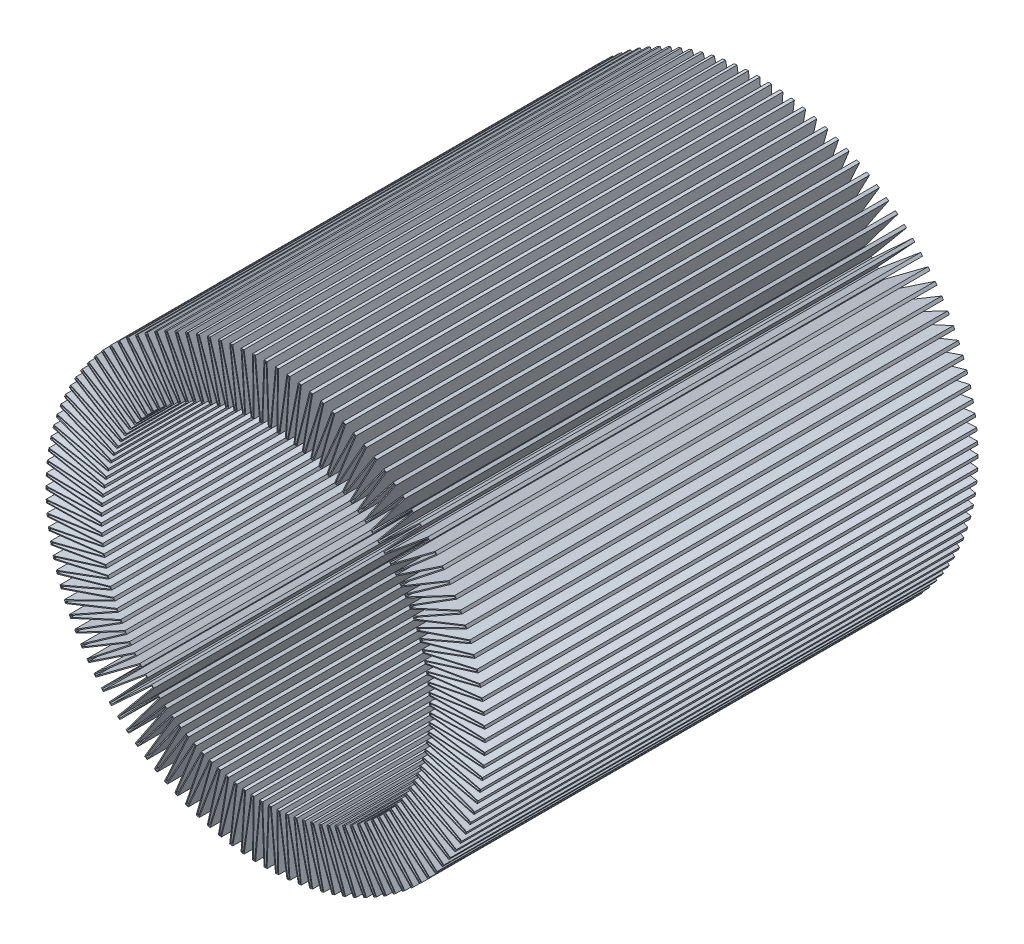
SolidWorks part; units mm, degrees
ref_plane "Front Plane" through (0, 0, 0) normal (0, 0, 1) x (1, 0, 0)
ref_plane "Top Plane" through (0, 0, 0) normal (0, 1, 0) x (1, 0, 0)
ref_plane "Right Plane" through (0, 0, 0) normal (1, 0, 0) x (0, 0, -1)
sketch "Sketch1" plane through (0, 0, 0) normal (0, 0, 1) x (1, 0, 0)
  line L0 (200.3975, -1.3849) -> (200.3975, 1.3849)
  line L1 (200.3975, 1.3849) -> (150.3615, 3.3121)
  line L2 (150.3615, 3.3121) -> (150.3288, 4.5618)
  line L3 (150.3288, 4.5618) -> (200.1953, 9.105)
  line L4 (200.1953, 9.105) -> (200.0504, 11.871)
  line L5 (200.0504, 11.871) -> (149.9821, 11.1769)
  line L6 (149.9821, 11.1769) -> (149.884, 12.4231)
  line L7 (149.884, 12.4231) -> (199.4445, 19.5699)
  line L8 (199.4445, 19.5699) -> (199.1549, 22.3245)
  line L9 (199.1549, 22.3245) -> (149.1916, 19.011)
  line L10 (149.1916, 19.011) -> (149.0284, 20.2504)
  line L11 (149.0284, 20.2504) -> (198.1469, 29.9812)
  line L12 (198.1469, 29.9812) -> (197.7136, 32.7169)
  line L13 (197.7136, 32.7169) -> (147.9922, 26.793)
  line L14 (147.9922, 26.793) -> (147.7644, 28.0222)
  line L15 (147.7644, 28.0222) -> (196.3063, 40.3104)
  line L16 (196.3063, 40.3104) -> (195.7304, 43.0196)
  line L17 (195.7304, 43.0196) -> (146.3871, 34.5016)
  line L18 (146.3871, 34.5016) -> (146.0953, 35.7172)
  line L19 (146.0953, 35.7172) -> (193.9276, 50.529)
  line L20 (193.9276, 50.529) -> (193.2107, 53.2044)
  line L21 (193.2107, 53.2044) -> (144.3808, 42.1156)
  line L22 (144.3808, 42.1156) -> (144.0258, 43.3143)
  line L23 (144.0258, 43.3143) -> (191.0173, 60.6091)
  line L24 (191.0173, 60.6091) -> (190.1614, 63.2433)
  line L25 (190.1614, 63.2433) -> (141.9788, 49.6142)
  line L26 (141.9788, 49.6142) -> (141.5615, 50.7926)
  line L27 (141.5615, 50.7926) -> (187.5835, 70.5231)
  line L28 (187.5835, 70.5231) -> (186.5909, 73.1089)
  line L29 (186.5909, 73.1089) -> (139.1876, 56.9768)
  line L30 (139.1876, 56.9768) -> (138.7092, 58.1318)
  line L31 (138.7092, 58.1318) -> (183.6355, 80.2439)
  line L32 (183.6355, 80.2439) -> (182.5089, 82.7742)
  line L33 (182.5089, 82.7742) -> (136.0149, 64.1833)
  line L34 (136.0149, 64.1833) -> (135.4767, 65.3116)
  line L35 (135.4767, 65.3116) -> (179.1842, 89.7446)
  line L36 (179.1842, 89.7446) -> (177.9268, 92.2125)
  line L37 (177.9268, 92.2125) -> (132.4694, 71.2138)
  line L38 (132.4694, 71.2138) -> (131.8729, 72.3124)
  line L39 (131.8729, 72.3124) -> (174.2418, 98.9994)
  line L40 (174.2418, 98.9994) -> (172.8569, 101.3981)
  line L41 (172.8569, 101.3981) -> (128.5608, 78.0491)
  line L42 (128.5608, 78.0491) -> (127.9076, 79.115)
  line L43 (127.9076, 79.115) -> (168.8217, 107.9828)
  line L44 (168.8217, 107.9828) -> (167.3132, 110.3058)
  line L45 (167.3132, 110.3058) -> (124.2999, 84.6705)
  line L46 (124.2999, 84.6705) -> (123.5918, 85.7007)
  line L47 (123.5918, 85.7007) -> (162.939, 116.6703)
  line L48 (162.939, 116.6703) -> (161.311, 118.9111)
  line L49 (161.311, 118.9111) -> (119.6982, 91.0598)
  line L50 (119.6982, 91.0598) -> (118.9372, 92.0516)
  line L51 (118.9372, 92.0516) -> (156.6096, 125.038)
  line L52 (156.6096, 125.038) -> (154.8666, 127.1905)
  line L53 (154.8666, 127.1905) -> (114.7685, 97.1995)
  line L54 (114.7685, 97.1995) -> (113.9566, 98.1501)
  line L55 (113.9566, 98.1501) -> (149.851, 133.0629)
  line L56 (149.851, 133.0629) -> (147.9977, 135.1213)
  line L57 (147.9977, 135.1213) -> (109.5242, 103.0728)
  line L58 (109.5242, 103.0728) -> (108.6636, 103.9796)
  line L59 (108.6636, 103.9796) -> (142.6817, 140.7232)
  line L60 (142.6817, 140.7232) -> (140.7232, 142.6817)
  line L61 (140.7232, 142.6817) -> (103.9796, 108.6636)
  line L62 (103.9796, 108.6636) -> (103.0728, 109.5242)
  line L63 (103.0728, 109.5242) -> (135.1213, 147.9977)
  line L64 (135.1213, 147.9977) -> (133.0629, 149.851)
  line L65 (133.0629, 149.851) -> (98.1501, 113.9566)
  line L66 (98.1501, 113.9566) -> (97.1995, 114.7685)
  line L67 (97.1995, 114.7685) -> (127.1905, 154.8666)
  line L68 (127.1905, 154.8666) -> (125.038, 156.6096)
  line L69 (125.038, 156.6096) -> (92.0516, 118.9372)
  line L70 (92.0516, 118.9372) -> (91.0598, 119.6982)
  line L71 (91.0598, 119.6982) -> (118.9111, 161.311)
  line L72 (118.9111, 161.311) -> (116.6703, 162.939)
  line L73 (116.6703, 162.939) -> (85.7007, 123.5918)
  line L74 (85.7007, 123.5918) -> (84.6705, 124.2999)
  line L75 (84.6705, 124.2999) -> (110.3058, 167.3132)
  line L76 (110.3058, 167.3132) -> (107.9828, 168.8217)
  line L77 (107.9828, 168.8217) -> (79.115, 127.9076)
  line L78 (79.115, 127.9076) -> (78.0491, 128.5608)
  line L79 (78.0491, 128.5608) -> (101.3981, 172.8569)
  line L80 (101.3981, 172.8569) -> (98.9994, 174.2418)
  line L81 (98.9994, 174.2418) -> (72.3124, 131.8729)
  line L82 (72.3124, 131.8729) -> (71.2138, 132.4694)
  line L83 (71.2138, 132.4694) -> (92.2125, 177.9268)
  line L84 (92.2125, 177.9268) -> (89.7446, 179.1842)
  line L85 (89.7446, 179.1842) -> (65.3116, 135.4767)
  line L86 (65.3116, 135.4767) -> (64.1833, 136.0149)
  line L87 (64.1833, 136.0149) -> (82.7742, 182.5089)
  line L88 (82.7742, 182.5089) -> (80.2439, 183.6355)
  line L89 (80.2439, 183.6355) -> (58.1318, 138.7092)
  line L90 (58.1318, 138.7092) -> (56.9768, 139.1876)
  line L91 (56.9768, 139.1876) -> (73.1089, 186.5909)
  line L92 (73.1089, 186.5909) -> (70.5231, 187.5835)
  line L93 (70.5231, 187.5835) -> (50.7926, 141.5615)
  line L94 (50.7926, 141.5615) -> (49.6142, 141.9788)
  line L95 (49.6142, 141.9788) -> (63.2433, 190.1614)
  line L96 (63.2433, 190.1614) -> (60.6091, 191.0173)
  line L97 (60.6091, 191.0173) -> (43.3143, 144.0258)
  line L98 (43.3143, 144.0258) -> (42.1156, 144.3808)
  line L99 (42.1156, 144.3808) -> (53.2044, 193.2107)
  line L100 (53.2044, 193.2107) -> (50.529, 193.9276)
  line L101 (50.529, 193.9276) -> (35.7172, 146.0953)
  line L102 (35.7172, 146.0953) -> (34.5016, 146.3871)
  line L103 (34.5016, 146.3871) -> (43.0196, 195.7304)
  line L104 (43.0196, 195.7304) -> (40.3104, 196.3063)
  line L105 (40.3104, 196.3063) -> (28.0222, 147.7644)
  line L106 (28.0222, 147.7644) -> (26.793, 147.9922)
  line L107 (26.793, 147.9922) -> (32.7169, 197.7136)
  line L108 (32.7169, 197.7136) -> (29.9812, 198.1469)
  line L109 (29.9812, 198.1469) -> (20.2504, 149.0284)
  line L110 (20.2504, 149.0284) -> (19.011, 149.1916)
  line L111 (19.011, 149.1916) -> (22.3245, 199.1549)
  line L112 (22.3245, 199.1549) -> (19.5699, 199.4445)
  line L113 (19.5699, 199.4445) -> (12.4231, 149.884)
  line L114 (12.4231, 149.884) -> (11.1769, 149.9821)
  line L115 (11.1769, 149.9821) -> (11.871, 200.0504)
  line L116 (11.871, 200.0504) -> (9.105, 200.1953)
  line L117 (9.105, 200.1953) -> (4.5618, 150.3288)
  line L118 (4.5618, 150.3288) -> (3.3121, 150.3615)
  line L119 (3.3121, 150.3615) -> (1.3849, 200.3975)
  line L120 (1.3849, 200.3975) -> (-1.3849, 200.3975)
  line L121 (-1.3849, 200.3975) -> (-3.3121, 150.3615)
  line L122 (-3.3121, 150.3615) -> (-4.5618, 150.3288)
  line L123 (-4.5618, 150.3288) -> (-9.105, 200.1953)
  line L124 (-9.105, 200.1953) -> (-11.871, 200.0504)
  line L125 (-11.871, 200.0504) -> (-11.1769, 149.9821)
  line L126 (-11.1769, 149.9821) -> (-12.4231, 149.884)
  line L127 (-12.4231, 149.884) -> (-19.5699, 199.4445)
  line L128 (-19.5699, 199.4445) -> (-22.3245, 199.1549)
  line L129 (-22.3245, 199.1549) -> (-19.011, 149.1916)
  line L130 (-19.011, 149.1916) -> (-20.2504, 149.0284)
  line L131 (-20.2504, 149.0284) -> (-29.9812, 198.1469)
  line L132 (-29.9812, 198.1469) -> (-32.7169, 197.7136)
  line L133 (-32.7169, 197.7136) -> (-26.793, 147.9922)
  line L134 (-26.793, 147.9922) -> (-28.0222, 147.7644)
  line L135 (-28.0222, 147.7644) -> (-40.3104, 196.3063)
  line L136 (-40.3104, 196.3063) -> (-43.0196, 195.7304)
  line L137 (-43.0196, 195.7304) -> (-34.5016, 146.3871)
  line L138 (-34.5016, 146.3871) -> (-35.7172, 146.0953)
  line L139 (-35.7172, 146.0953) -> (-50.529, 193.9276)
  line L140 (-50.529, 193.9276) -> (-53.2044, 193.2107)
  line L141 (-53.2044, 193.2107) -> (-42.1156, 144.3808)
  line L142 (-42.1156, 144.3808) -> (-43.3143, 144.0258)
  line L143 (-43.3143, 144.0258) -> (-60.6091, 191.0173)
  line L144 (-60.6091, 191.0173) -> (-63.2433, 190.1614)
  line L145 (-63.2433, 190.1614) -> (-49.6142, 141.9788)
  line L146 (-49.6142, 141.9788) -> (-50.7926, 141.5615)
  line L147 (-50.7926, 141.5615) -> (-70.5231, 187.5835)
  line L148 (-70.5231, 187.5835) -> (-73.1089, 186.5909)
  line L149 (-73.1089, 186.5909) -> (-56.9768, 139.1876)
  line L150 (-56.9768, 139.1876) -> (-58.1318, 138.7092)
  line L151 (-58.1318, 138.7092) -> (-80.2439, 183.6355)
  line L152 (-80.2439, 183.6355) -> (-82.7742, 182.5089)
  line L153 (-82.7742, 182.5089) -> (-64.1833, 136.0149)
  line L154 (-64.1833, 136.0149) -> (-65.3116, 135.4767)
  line L155 (-65.3116, 135.4767) -> (-89.7446, 179.1842)
  line L156 (-89.7446, 179.1842) -> (-92.2125, 177.9268)
  line L157 (-92.2125, 177.9268) -> (-71.2138, 132.4694)
  line L158 (-71.2138, 132.4694) -> (-72.3124, 131.8729)
  line L159 (-72.3124, 131.8729) -> (-98.9994, 174.2418)
  line L160 (-98.9994, 174.2418) -> (-101.3981, 172.8569)
  line L161 (-101.3981, 172.8569) -> (-78.0491, 128.5608)
  line L162 (-78.0491, 128.5608) -> (-79.115, 127.9076)
  line L163 (-79.115, 127.9076) -> (-107.9828, 168.8217)
  line L164 (-107.9828, 168.8217) -> (-110.3058, 167.3132)
  line L165 (-110.3058, 167.3132) -> (-84.6705, 124.2999)
  line L166 (-84.6705, 124.2999) -> (-85.7007, 123.5918)
  line L167 (-85.7007, 123.5918) -> (-116.6703, 162.939)
  line L168 (-116.6703, 162.939) -> (-118.9111, 161.311)
  line L169 (-118.9111, 161.311) -> (-91.0598, 119.6982)
  line L170 (-91.0598, 119.6982) -> (-92.0516, 118.9372)
  line L171 (-92.0516, 118.9372) -> (-125.038, 156.6096)
  line L172 (-125.038, 156.6096) -> (-127.1905, 154.8666)
  line L173 (-127.1905, 154.8666) -> (-97.1995, 114.7685)
  line L174 (-97.1995, 114.7685) -> (-98.1501, 113.9566)
  line L175 (-98.1501, 113.9566) -> (-133.0629, 149.851)
  line L176 (-133.0629, 149.851) -> (-135.1213, 147.9977)
  line L177 (-135.1213, 147.9977) -> (-103.0728, 109.5242)
  line L178 (-103.0728, 109.5242) -> (-103.9796, 108.6636)
  line L179 (-103.9796, 108.6636) -> (-140.7232, 142.6817)
  line L180 (-140.7232, 142.6817) -> (-142.6817, 140.7232)
  line L181 (-142.6817, 140.7232) -> (-108.6636, 103.9796)
  line L182 (-108.6636, 103.9796) -> (-109.5242, 103.0728)
  line L183 (-109.5242, 103.0728) -> (-147.9977, 135.1213)
  line L184 (-147.9977, 135.1213) -> (-149.851, 133.0629)
  line L185 (-149.851, 133.0629) -> (-113.9566, 98.1501)
  line L186 (-113.9566, 98.1501) -> (-114.7685, 97.1995)
  line L187 (-114.7685, 97.1995) -> (-154.8666, 127.1905)
  line L188 (-154.8666, 127.1905) -> (-156.6096, 125.038)
  line L189 (-156.6096, 125.038) -> (-118.9372, 92.0516)
  line L190 (-118.9372, 92.0516) -> (-119.6982, 91.0598)
  line L191 (-119.6982, 91.0598) -> (-161.311, 118.9111)
  line L192 (-161.311, 118.9111) -> (-162.939, 116.6703)
  line L193 (-162.939, 116.6703) -> (-123.5918, 85.7007)
  line L194 (-123.5918, 85.7007) -> (-124.2999, 84.6705)
  line L195 (-124.2999, 84.6705) -> (-167.3132, 110.3058)
  line L196 (-167.3132, 110.3058) -> (-168.8217, 107.9828)
  line L197 (-168.8217, 107.9828) -> (-127.9076, 79.115)
  line L198 (-127.9076, 79.115) -> (-128.5608, 78.0491)
  line L199 (-128.5608, 78.0491) -> (-172.8569, 101.3981)
  line L200 (-172.8569, 101.3981) -> (-174.2418, 98.9994)
  line L201 (-174.2418, 98.9994) -> (-131.8729, 72.3124)
  line L202 (-131.8729, 72.3124) -> (-132.4694, 71.2138)
  line L203 (-132.4694, 71.2138) -> (-177.9268, 92.2125)
  line L204 (-177.9268, 92.2125) -> (-179.1842, 89.7446)
  line L205 (-179.1842, 89.7446) -> (-135.4767, 65.3116)
  line L206 (-135.4767, 65.3116) -> (-136.0149, 64.1833)
  line L207 (-136.0149, 64.1833) -> (-182.5089, 82.7742)
  line L208 (-182.5089, 82.7742) -> (-183.6355, 80.2439)
  line L209 (-183.6355, 80.2439) -> (-138.7092, 58.1318)
  line L210 (-138.7092, 58.1318) -> (-139.1876, 56.9768)
  line L211 (-139.1876, 56.9768) -> (-186.5909, 73.1089)
  line L212 (-186.5909, 73.1089) -> (-187.5835, 70.5231)
  line L213 (-187.5835, 70.5231) -> (-141.5615, 50.7926)
  line L214 (-141.5615, 50.7926) -> (-141.9788, 49.6142)
  line L215 (-141.9788, 49.6142) -> (-190.1614, 63.2433)
  line L216 (-190.1614, 63.2433) -> (-191.0173, 60.6091)
  line L217 (-191.0173, 60.6091) -> (-144.0258, 43.3143)
  line L218 (-144.0258, 43.3143) -> (-144.3808, 42.1156)
  line L219 (-144.3808, 42.1156) -> (-193.2107, 53.2044)
  line L220 (-193.2107, 53.2044) -> (-193.9276, 50.529)
  line L221 (-193.9276, 50.529) -> (-146.0953, 35.7172)
  line L222 (-146.0953, 35.7172) -> (-146.3871, 34.5016)
  line L223 (-146.3871, 34.5016) -> (-195.7304, 43.0196)
  line L224 (-195.7304, 43.0196) -> (-196.3063, 40.3104)
  line L225 (-196.3063, 40.3104) -> (-147.7644, 28.0222)
  line L226 (-147.7644, 28.0222) -> (-147.9922, 26.793)
  line L227 (-147.9922, 26.793) -> (-197.7136, 32.7169)
  line L228 (-197.7136, 32.7169) -> (-198.1469, 29.9812)
  line L229 (-198.1469, 29.9812) -> (-149.0284, 20.2504)
  line L230 (-149.0284, 20.2504) -> (-149.1916, 19.011)
  line L231 (-149.1916, 19.011) -> (-199.1549, 22.3245)
  line L232 (-199.1549, 22.3245) -> (-199.4445, 19.5699)
  line L233 (-199.4445, 19.5699) -> (-149.884, 12.4231)
  line L234 (-149.884, 12.4231) -> (-149.9821, 11.1769)
  line L235 (-149.9821, 11.1769) -> (-200.0504, 11.871)
  line L236 (-200.0504, 11.871) -> (-200.1953, 9.105)
  line L237 (-200.1953, 9.105) -> (-150.3288, 4.5618)
  line L238 (-150.3288, 4.5618) -> (-150.3615, 3.3121)
  line L239 (-150.3615, 3.3121) -> (-200.3975, 1.3849)
  line L240 (-200.3975, 1.3849) -> (-200.3975, -1.3849)
  line L241 (-200.3975, -1.3849) -> (-150.3615, -3.3121)
  line L242 (-150.3615, -3.3121) -> (-150.3288, -4.5618)
  line L243 (-150.3288, -4.5618) -> (-200.1953, -9.105)
  line L244 (-200.1953, -9.105) -> (-200.0504, -11.871)
  line L245 (-200.0504, -11.871) -> (-149.9821, -11.1769)
  line L246 (-149.9821, -11.1769) -> (-149.884, -12.4231)
  line L247 (-149.884, -12.4231) -> (-199.4445, -19.5699)
  line L248 (-199.4445, -19.5699) -> (-199.1549, -22.3245)
  line L249 (-199.1549, -22.3245) -> (-149.1916, -19.011)
  line L250 (-149.1916, -19.011) -> (-149.0284, -20.2504)
  line L251 (-149.0284, -20.2504) -> (-198.1469, -29.9812)
  line L252 (-198.1469, -29.9812) -> (-197.7136, -32.7169)
  line L253 (-197.7136, -32.7169) -> (-147.9922, -26.793)
  line L254 (-147.9922, -26.793) -> (-147.7644, -28.0222)
  line L255 (-147.7644, -28.0222) -> (-196.3063, -40.3104)
  line L256 (-196.3063, -40.3104) -> (-195.7304, -43.0196)
  line L257 (-195.7304, -43.0196) -> (-146.3871, -34.5016)
  line L258 (-146.3871, -34.5016) -> (-146.0953, -35.7172)
  line L259 (-146.0953, -35.7172) -> (-193.9276, -50.529)
  line L260 (-193.9276, -50.529) -> (-193.2107, -53.2044)
  line L261 (-193.2107, -53.2044) -> (-144.3808, -42.1156)
  line L262 (-144.3808, -42.1156) -> (-144.0258, -43.3143)
  line L263 (-144.0258, -43.3143) -> (-191.0173, -60.6091)
  line L264 (-191.0173, -60.6091) -> (-190.1614, -63.2433)
  line L265 (-190.1614, -63.2433) -> (-141.9788, -49.6142)
  line L266 (-141.9788, -49.6142) -> (-141.5615, -50.7926)
  line L267 (-141.5615, -50.7926) -> (-187.5835, -70.5231)
  line L268 (-187.5835, -70.5231) -> (-186.5909, -73.1089)
  line L269 (-186.5909, -73.1089) -> (-139.1876, -56.9768)
  line L270 (-139.1876, -56.9768) -> (-138.7092, -58.1318)
  line L271 (-138.7092, -58.1318) -> (-183.6355, -80.2439)
  line L272 (-183.6355, -80.2439) -> (-182.5089, -82.7742)
  line L273 (-182.5089, -82.7742) -> (-136.0149, -64.1833)
  line L274 (-136.0149, -64.1833) -> (-135.4767, -65.3116)
  line L275 (-135.4767, -65.3116) -> (-179.1842, -89.7446)
  line L276 (-179.1842, -89.7446) -> (-177.9268, -92.2125)
  line L277 (-177.9268, -92.2125) -> (-132.4694, -71.2138)
  line L278 (-132.4694, -71.2138) -> (-131.8729, -72.3124)
  line L279 (-131.8729, -72.3124) -> (-174.2418, -98.9994)
  line L280 (-174.2418, -98.9994) -> (-172.8569, -101.3981)
  line L281 (-172.8569, -101.3981) -> (-128.5608, -78.0491)
  line L282 (-128.5608, -78.0491) -> (-127.9076, -79.115)
  line L283 (-127.9076, -79.115) -> (-168.8217, -107.9828)
  line L284 (-168.8217, -107.9828) -> (-167.3132, -110.3058)
  line L285 (-167.3132, -110.3058) -> (-124.2999, -84.6705)
  line L286 (-124.2999, -84.6705) -> (-123.5918, -85.7007)
  line L287 (-123.5918, -85.7007) -> (-162.939, -116.6703)
  line L288 (-162.939, -116.6703) -> (-161.311, -118.9111)
  line L289 (-161.311, -118.9111) -> (-119.6982, -91.0598)
  line L290 (-119.6982, -91.0598) -> (-118.9372, -92.0516)
  line L291 (-118.9372, -92.0516) -> (-156.6096, -125.038)
  line L292 (-156.6096, -125.038) -> (-154.8666, -127.1905)
  line L293 (-154.8666, -127.1905) -> (-114.7685, -97.1995)
  line L294 (-114.7685, -97.1995) -> (-113.9566, -98.1501)
  line L295 (-113.9566, -98.1501) -> (-149.851, -133.0629)
  line L296 (-149.851, -133.0629) -> (-147.9977, -135.1213)
  line L297 (-147.9977, -135.1213) -> (-109.5242, -103.0728)
  line L298 (-109.5242, -103.0728) -> (-108.6636, -103.9796)
  line L299 (-108.6636, -103.9796) -> (-142.6817, -140.7232)
  line L300 (-142.6817, -140.7232) -> (-140.7232, -142.6817)
  line L301 (-140.7232, -142.6817) -> (-103.9796, -108.6636)
  line L302 (-103.9796, -108.6636) -> (-103.0728, -109.5242)
  line L303 (-103.0728, -109.5242) -> (-135.1213, -147.9977)
  line L304 (-135.1213, -147.9977) -> (-133.0629, -149.851)
  line L305 (-133.0629, -149.851) -> (-98.1501, -113.9566)
  line L306 (-98.1501, -113.9566) -> (-97.1995, -114.7685)
  line L307 (-97.1995, -114.7685) -> (-127.1905, -154.8666)
  line L308 (-127.1905, -154.8666) -> (-125.038, -156.6096)
  line L309 (-125.038, -156.6096) -> (-92.0516, -118.9372)
  line L310 (-92.0516, -118.9372) -> (-91.0598, -119.6982)
  line L311 (-91.0598, -119.6982) -> (-118.9111, -161.311)
  line L312 (-118.9111, -161.311) -> (-116.6703, -162.939)
  line L313 (-116.6703, -162.939) -> (-85.7007, -123.5918)
  line L314 (-85.7007, -123.5918) -> (-84.6705, -124.2999)
  line L315 (-84.6705, -124.2999) -> (-110.3058, -167.3132)
  line L316 (-110.3058, -167.3132) -> (-107.9828, -168.8217)
  line L317 (-107.9828, -168.8217) -> (-79.115, -127.9076)
  line L318 (-79.115, -127.9076) -> (-78.0491, -128.5608)
  line L319 (-78.0491, -128.5608) -> (-101.3981, -172.8569)
  line L320 (-101.3981, -172.8569) -> (-98.9994, -174.2418)
  line L321 (-98.9994, -174.2418) -> (-72.3124, -131.8729)
  line L322 (-72.3124, -131.8729) -> (-71.2138, -132.4694)
  line L323 (-71.2138, -132.4694) -> (-92.2125, -177.9268)
  line L324 (-92.2125, -177.9268) -> (-89.7446, -179.1842)
  line L325 (-89.7446, -179.1842) -> (-65.3116, -135.4767)
  line L326 (-65.3116, -135.4767) -> (-64.1833, -136.0149)
  line L327 (-64.1833, -136.0149) -> (-82.7742, -182.5089)
  line L328 (-82.7742, -182.5089) -> (-80.2439, -183.6355)
  line L329 (-80.2439, -183.6355) -> (-58.1318, -138.7092)
  line L330 (-58.1318, -138.7092) -> (-56.9768, -139.1876)
  line L331 (-56.9768, -139.1876) -> (-73.1089, -186.5909)
  line L332 (-73.1089, -186.5909) -> (-70.5231, -187.5835)
  line L333 (-70.5231, -187.5835) -> (-50.7926, -141.5615)
  line L334 (-50.7926, -141.5615) -> (-49.6142, -141.9788)
  line L335 (-49.6142, -141.9788) -> (-63.2433, -190.1614)
  line L336 (-63.2433, -190.1614) -> (-60.6091, -191.0173)
  line L337 (-60.6091, -191.0173) -> (-43.3143, -144.0258)
  line L338 (-43.3143, -144.0258) -> (-42.1156, -144.3808)
  line L339 (-42.1156, -144.3808) -> (-53.2044, -193.2107)
  line L340 (-53.2044, -193.2107) -> (-50.529, -193.9276)
  line L341 (-50.529, -193.9276) -> (-35.7172, -146.0953)
  line L342 (-35.7172, -146.0953) -> (-34.5016, -146.3871)
  line L343 (-34.5016, -146.3871) -> (-43.0196, -195.7304)
  line L344 (-43.0196, -195.7304) -> (-40.3104, -196.3063)
  line L345 (-40.3104, -196.3063) -> (-28.0222, -147.7644)
  line L346 (-28.0222, -147.7644) -> (-26.793, -147.9922)
  line L347 (-26.793, -147.9922) -> (-32.7169, -197.7136)
  line L348 (-32.7169, -197.7136) -> (-29.9812, -198.1469)
  line L349 (-29.9812, -198.1469) -> (-20.2504, -149.0284)
  line L350 (-20.2504, -149.0284) -> (-19.011, -149.1916)
  line L351 (-19.011, -149.1916) -> (-22.3245, -199.1549)
  line L352 (-22.3245, -199.1549) -> (-19.5699, -199.4445)
  line L353 (-19.5699, -199.4445) -> (-12.4231, -149.884)
  line L354 (-12.4231, -149.884) -> (-11.1769, -149.9821)
  line L355 (-11.1769, -149.9821) -> (-11.871, -200.0504)
  line L356 (-11.871, -200.0504) -> (-9.105, -200.1953)
  line L357 (-9.105, -200.1953) -> (-4.5618, -150.3288)
  line L358 (-4.5618, -150.3288) -> (-3.3121, -150.3615)
  line L359 (-3.3121, -150.3615) -> (-1.3849, -200.3975)
  line L360 (-1.3849, -200.3975) -> (1.3849, -200.3975)
  line L361 (1.3849, -200.3975) -> (3.3121, -150.3615)
  line L362 (3.3121, -150.3615) -> (4.5618, -150.3288)
  line L363 (4.5618, -150.3288) -> (9.105, -200.1953)
  line L364 (9.105, -200.1953) -> (11.871, -200.0504)
  line L365 (11.871, -200.0504) -> (11.1769, -149.9821)
  line L366 (11.1769, -149.9821) -> (12.4231, -149.884)
  line L367 (12.4231, -149.884) -> (19.5699, -199.4445)
  line L368 (19.5699, -199.4445) -> (22.3245, -199.1549)
  line L369 (22.3245, -199.1549) -> (19.011, -149.1916)
  line L370 (19.011, -149.1916) -> (20.2504, -149.0284)
  line L371 (20.2504, -149.0284) -> (29.9812, -198.1469)
  line L372 (29.9812, -198.1469) -> (32.7169, -197.7136)
  line L373 (32.7169, -197.7136) -> (26.793, -147.9922)
  line L374 (26.793, -147.9922) -> (28.0222, -147.7644)
  line L375 (28.0222, -147.7644) -> (40.3104, -196.3063)
  line L376 (40.3104, -196.3063) -> (43.0196, -195.7304)
  line L377 (43.0196, -195.7304) -> (34.5016, -146.3871)
  line L378 (34.5016, -146.3871) -> (35.7172, -146.0953)
  line L379 (35.7172, -146.0953) -> (50.529, -193.9276)
  line L380 (50.529, -193.9276) -> (53.2044, -193.2107)
  line L381 (53.2044, -193.2107) -> (42.1156, -144.3808)
  line L382 (42.1156, -144.3808) -> (43.3143, -144.0258)
  line L383 (43.3143, -144.0258) -> (60.6091, -191.0173)
  line L384 (60.6091, -191.0173) -> (63.2433, -190.1614)
  line L385 (63.2433, -190.1614) -> (49.6142, -141.9788)
  line L386 (49.6142, -141.9788) -> (50.7926, -141.5615)
  line L387 (50.7926, -141.5615) -> (70.5231, -187.5835)
  line L388 (70.5231, -187.5835) -> (73.1089, -186.5909)
  line L389 (73.1089, -186.5909) -> (56.9768, -139.1876)
  line L390 (56.9768, -139.1876) -> (58.1318, -138.7092)
  line L391 (58.1318, -138.7092) -> (80.2439, -183.6355)
  line L392 (80.2439, -183.6355) -> (82.7742, -182.5089)
  line L393 (82.7742, -182.5089) -> (64.1833, -136.0149)
  line L394 (64.1833, -136.0149) -> (65.3116, -135.4767)
  line L395 (65.3116, -135.4767) -> (89.7446, -179.1842)
  line L396 (89.7446, -179.1842) -> (92.2125, -177.9268)
  line L397 (92.2125, -177.9268) -> (71.2138, -132.4694)
  line L398 (71.2138, -132.4694) -> (72.3124, -131.8729)
  line L399 (72.3124, -131.8729) -> (98.9994, -174.2418)
  line L400 (98.9994, -174.2418) -> (101.3981, -172.8569)
  line L401 (101.3981, -172.8569) -> (78.0491, -128.5608)
  line L402 (78.0491, -128.5608) -> (79.115, -127.9076)
  line L403 (79.115, -127.9076) -> (107.9828, -168.8217)
  line L404 (107.9828, -168.8217) -> (110.3058, -167.3132)
  line L405 (110.3058, -167.3132) -> (84.6705, -124.2999)
  line L406 (84.6705, -124.2999) -> (85.7007, -123.5918)
  line L407 (85.7007, -123.5918) -> (116.6703, -162.939)
  line L408 (116.6703, -162.939) -> (118.9111, -161.311)
  line L409 (118.9111, -161.311) -> (91.0598, -119.6982)
  line L410 (91.0598, -119.6982) -> (92.0516, -118.9372)
  line L411 (92.0516, -118.9372) -> (125.038, -156.6096)
  line L412 (125.038, -156.6096) -> (127.1905, -154.8666)
  line L413 (127.1905, -154.8666) -> (97.1995, -114.7685)
  line L414 (97.1995, -114.7685) -> (98.1501, -113.9566)
  line L415 (98.1501, -113.9566) -> (133.0629, -149.851)
  line L416 (133.0629, -149.851) -> (135.1213, -147.9977)
  line L417 (135.1213, -147.9977) -> (103.0728, -109.5242)
  line L418 (103.0728, -109.5242) -> (103.9796, -108.6636)
  line L419 (103.9796, -108.6636) -> (140.7232, -142.6817)
  line L420 (140.7232, -142.6817) -> (142.6817, -140.7232)
  line L421 (142.6817, -140.7232) -> (108.6636, -103.9796)
  line L422 (108.6636, -103.9796) -> (109.5242, -103.0728)
  line L423 (109.5242, -103.0728) -> (147.9977, -135.1213)
  line L424 (147.9977, -135.1213) -> (149.851, -133.0629)
  line L425 (149.851, -133.0629) -> (113.9566, -98.1501)
  line L426 (113.9566, -98.1501) -> (114.7685, -97.1995)
  line L427 (114.7685, -97.1995) -> (154.8666, -127.1905)
  line L428 (154.8666, -127.1905) -> (156.6096, -125.038)
  line L429 (156.6096, -125.038) -> (118.9372, -92.0516)
  line L430 (118.9372, -92.0516) -> (119.6982, -91.0598)
  line L431 (119.6982, -91.0598) -> (161.311, -118.9111)
  line L432 (161.311, -118.9111) -> (162.939, -116.6703)
  line L433 (162.939, -116.6703) -> (123.5918, -85.7007)
  line L434 (123.5918, -85.7007) -> (124.2999, -84.6705)
  line L435 (124.2999, -84.6705) -> (167.3132, -110.3058)
  line L436 (167.3132, -110.3058) -> (168.8217, -107.9828)
  line L437 (168.8217, -107.9828) -> (127.9076, -79.115)
  line L438 (127.9076, -79.115) -> (128.5608, -78.0491)
  line L439 (128.5608, -78.0491) -> (172.8569, -101.3981)
  line L440 (172.8569, -101.3981) -> (174.2418, -98.9994)
  line L441 (174.2418, -98.9994) -> (131.8729, -72.3124)
  line L442 (131.8729, -72.3124) -> (132.4694, -71.2138)
  line L443 (132.4694, -71.2138) -> (177.9268, -92.2125)
  line L444 (177.9268, -92.2125) -> (179.1842, -89.7446)
  line L445 (179.1842, -89.7446) -> (135.4767, -65.3116)
  line L446 (135.4767, -65.3116) -> (136.0149, -64.1833)
  line L447 (136.0149, -64.1833) -> (182.5089, -82.7742)
  line L448 (182.5089, -82.7742) -> (183.6355, -80.2439)
  line L449 (183.6355, -80.2439) -> (138.7092, -58.1318)
  line L450 (138.7092, -58.1318) -> (139.1876, -56.9768)
  line L451 (139.1876, -56.9768) -> (186.5909, -73.1089)
  line L452 (186.5909, -73.1089) -> (187.5835, -70.5231)
  line L453 (187.5835, -70.5231) -> (141.5615, -50.7926)
  line L454 (141.5615, -50.7926) -> (141.9788, -49.6142)
  line L455 (141.9788, -49.6142) -> (190.1614, -63.2433)
  line L456 (190.1614, -63.2433) -> (191.0173, -60.6091)
  line L457 (191.0173, -60.6091) -> (144.0258, -43.3143)
  line L458 (144.0258, -43.3143) -> (144.3808, -42.1156)
  line L459 (144.3808, -42.1156) -> (193.2107, -53.2044)
  line L460 (193.2107, -53.2044) -> (193.9276, -50.529)
  line L461 (193.9276, -50.529) -> (146.0953, -35.7172)
  line L462 (146.0953, -35.7172) -> (146.3871, -34.5016)
  line L463 (146.3871, -34.5016) -> (195.7304, -43.0196)
  line L464 (195.7304, -43.0196) -> (196.3063, -40.3104)
  line L465 (196.3063, -40.3104) -> (147.7644, -28.0222)
  line L466 (147.7644, -28.0222) -> (147.9922, -26.793)
  line L467 (147.9922, -26.793) -> (197.7136, -32.7169)
  line L468 (197.7136, -32.7169) -> (198.1469, -29.9812)
  line L469 (198.1469, -29.9812) -> (149.0284, -20.2504)
  line L470 (149.0284, -20.2504) -> (149.1916, -19.011)
  line L471 (149.1916, -19.011) -> (199.1549, -22.3245)
  line L472 (199.1549, -22.3245) -> (199.4445, -19.5699)
  line L473 (199.4445, -19.5699) -> (149.884, -12.4231)
  line L474 (149.884, -12.4231) -> (149.9821, -11.1769)
  line L475 (149.9821, -11.1769) -> (200.0504, -11.871)
  line L476 (200.0504, -11.871) -> (200.1953, -9.105)
  line L477 (200.1953, -9.105) -> (150.3288, -4.5618)
  line L478 (150.3288, -4.5618) -> (150.3615, -3.3121)
  line L479 (150.3615, -3.3121) -> (200.3975, -1.3849)
  line L480 (199.5975, -0.6151) -> (199.5975, 0.6151)
  line L481 (199.5975, 0.6151) -> (149.5814, 2.5415)
  line L482 (149.5814, 2.5415) -> (149.5094, 5.2904)
  line L483 (149.5094, 5.2904) -> (199.3562, 9.8319)
  line L484 (199.3562, 9.8319) -> (199.2918, 11.0604)
  line L485 (199.2918, 11.0604) -> (149.2434, 10.3665)
  line L486 (149.2434, 10.3665) -> (149.0276, 13.1079)
  line L487 (149.0276, 13.1079) -> (198.5684, 20.2519)
  line L488 (198.5684, 20.2519) -> (198.4398, 21.4754)
  line L489 (198.4398, 21.4754) -> (148.4963, 18.1631)
  line L490 (148.4963, 18.1631) -> (148.1374, 20.8894)
  line L491 (148.1374, 20.8894) -> (197.2363, 30.6164)
  line L492 (197.2363, 30.6164) -> (197.0439, 31.8315)
  line L493 (197.0439, 31.8315) -> (147.3422, 25.9099)
  line L494 (147.3422, 25.9099) -> (146.8411, 28.6137)
  line L495 (146.8411, 28.6137) -> (195.3637, 40.897)
  line L496 (195.3637, 40.897) -> (195.1079, 42.1003)
  line L497 (195.1079, 42.1003) -> (145.7843, 33.5857)
  line L498 (145.7843, 33.5857) -> (145.1423, 36.2596)
  line L499 (145.1423, 36.2596) -> (192.9556, 51.0655)
  line L500 (192.9556, 51.0655) -> (192.6372, 52.2538)
  line L501 (192.6372, 52.2538) -> (143.8267, 41.1694)
  line L502 (143.8267, 41.1694) -> (143.0457, 43.8061)
  line L503 (143.0457, 43.8061) -> (190.0186, 61.094)
  line L504 (190.0186, 61.094) -> (189.6384, 62.264)
  line L505 (189.6384, 62.264) -> (141.475, 48.6403)
  line L506 (141.475, 48.6403) -> (140.5571, 51.2325)
  line L507 (140.5571, 51.2325) -> (186.5608, 70.9551)
  line L508 (186.5608, 70.9551) -> (186.1199, 72.1036)
  line L509 (186.1199, 72.1036) -> (138.7355, 55.9779)
  line L510 (138.7355, 55.9779) -> (137.6831, 58.5184)
  line L511 (137.6831, 58.5184) -> (182.5916, 80.6217)
  line L512 (182.5916, 80.6217) -> (182.0912, 81.7455)
  line L513 (182.0912, 81.7455) -> (135.6157, 63.162)
  line L514 (135.6157, 63.162) -> (134.4318, 65.644)
  line L515 (134.4318, 65.644) -> (178.1219, 90.0673)
  line L516 (178.1219, 90.0673) -> (177.5634, 91.1634)
  line L517 (177.5634, 91.1634) -> (132.1242, 70.1731)
  line L518 (132.1242, 70.1731) -> (130.8121, 72.5897)
  line L519 (130.8121, 72.5897) -> (173.1641, 99.2661)
  line L520 (173.1641, 99.2661) -> (172.549, 100.3314)
  line L521 (172.549, 100.3314) -> (128.2705, 76.9917)
  line L522 (128.2705, 76.9917) -> (126.8337, 79.3364)
  line L523 (126.8337, 79.3364) -> (167.7316, 108.1927)
  line L524 (167.7316, 108.1927) -> (167.0615, 109.2245)
  line L525 (167.0615, 109.2245) -> (124.0653, 83.5994)
  line L526 (124.0653, 83.5994) -> (122.5078, 85.8656)
  line L527 (122.5078, 85.8656) -> (161.8393, 116.8228)
  line L528 (161.8393, 116.8228) -> (161.1162, 117.8181)
  line L529 (161.1162, 117.8181) -> (119.52, 89.9779)
  line L530 (119.52, 89.9779) -> (117.846, 92.1595)
  line L531 (117.846, 92.1595) -> (155.5035, 125.1327)
  line L532 (155.5035, 125.1327) -> (154.7293, 126.0888)
  line L533 (154.7293, 126.0888) -> (114.6471, 96.1098)
  line L534 (114.6471, 96.1098) -> (112.8613, 98.2008)
  line L535 (112.8613, 98.2008) -> (148.7414, 133.0997)
  line L536 (148.7414, 133.0997) -> (147.9183, 134.0139)
  line L537 (147.9183, 134.0139) -> (109.46, 101.9782)
  line L538 (109.46, 101.9782) -> (107.5672, 103.9729)
  line L539 (107.5672, 103.9729) -> (141.5717, 140.7018)
  line L540 (141.5717, 140.7018) -> (140.7018, 141.5717)
  line L541 (140.7018, 141.5717) -> (103.9729, 107.5672)
  line L542 (103.9729, 107.5672) -> (101.9782, 109.46)
  line L543 (101.9782, 109.46) -> (134.0139, 147.9183)
  line L544 (134.0139, 147.9183) -> (133.0997, 148.7414)
  line L545 (133.0997, 148.7414) -> (98.2008, 112.8613)
  line L546 (98.2008, 112.8613) -> (96.1098, 114.6471)
  line L547 (96.1098, 114.6471) -> (126.0888, 154.7293)
  line L548 (126.0888, 154.7293) -> (125.1327, 155.5035)
  line L549 (125.1327, 155.5035) -> (92.1595, 117.846)
  line L550 (92.1595, 117.846) -> (89.9779, 119.52)
  line L551 (89.9779, 119.52) -> (117.8181, 161.1162)
  line L552 (117.8181, 161.1162) -> (116.8228, 161.8393)
  line L553 (116.8228, 161.8393) -> (85.8656, 122.5078)
  line L554 (85.8656, 122.5078) -> (83.5994, 124.0653)
  line L555 (83.5994, 124.0653) -> (109.2245, 167.0615)
  line L556 (109.2245, 167.0615) -> (108.1927, 167.7316)
  line L557 (108.1927, 167.7316) -> (79.3364, 126.8337)
  line L558 (79.3364, 126.8337) -> (76.9917, 128.2705)
  line L559 (76.9917, 128.2705) -> (100.3314, 172.549)
  line L560 (100.3314, 172.549) -> (99.2661, 173.1641)
  line L561 (99.2661, 173.1641) -> (72.5897, 130.8121)
  line L562 (72.5897, 130.8121) -> (70.1731, 132.1242)
  line L563 (70.1731, 132.1242) -> (91.1634, 177.5634)
  line L564 (91.1634, 177.5634) -> (90.0673, 178.1219)
  line L565 (90.0673, 178.1219) -> (65.644, 134.4318)
  line L566 (65.644, 134.4318) -> (63.162, 135.6157)
  line L567 (63.162, 135.6157) -> (81.7455, 182.0912)
  line L568 (81.7455, 182.0912) -> (80.6217, 182.5916)
  line L569 (80.6217, 182.5916) -> (58.5184, 137.6831)
  line L570 (58.5184, 137.6831) -> (55.9779, 138.7355)
  line L571 (55.9779, 138.7355) -> (72.1036, 186.1199)
  line L572 (72.1036, 186.1199) -> (70.9551, 186.5608)
  line L573 (70.9551, 186.5608) -> (51.2325, 140.5571)
  line L574 (51.2325, 140.5571) -> (48.6403, 141.475)
  line L575 (48.6403, 141.475) -> (62.264, 189.6384)
  line L576 (62.264, 189.6384) -> (61.094, 190.0186)
  line L577 (61.094, 190.0186) -> (43.8061, 143.0457)
  line L578 (43.8061, 143.0457) -> (41.1694, 143.8267)
  line L579 (41.1694, 143.8267) -> (52.2538, 192.6372)
  line L580 (52.2538, 192.6372) -> (51.0655, 192.9556)
  line L581 (51.0655, 192.9556) -> (36.2596, 145.1423)
  line L582 (36.2596, 145.1423) -> (33.5857, 145.7843)
  line L583 (33.5857, 145.7843) -> (42.1003, 195.1079)
  line L584 (42.1003, 195.1079) -> (40.897, 195.3637)
  line L585 (40.897, 195.3637) -> (28.6137, 146.8411)
  line L586 (28.6137, 146.8411) -> (25.9099, 147.3422)
  line L587 (25.9099, 147.3422) -> (31.8315, 197.0439)
  line L588 (31.8315, 197.0439) -> (30.6164, 197.2363)
  line L589 (30.6164, 197.2363) -> (20.8894, 148.1374)
  line L590 (20.8894, 148.1374) -> (18.1631, 148.4963)
  line L591 (18.1631, 148.4963) -> (21.4754, 198.4398)
  line L592 (21.4754, 198.4398) -> (20.2519, 198.5684)
  line L593 (20.2519, 198.5684) -> (13.1079, 149.0276)
  line L594 (13.1079, 149.0276) -> (10.3665, 149.2434)
  line L595 (10.3665, 149.2434) -> (11.0604, 199.2918)
  line L596 (11.0604, 199.2918) -> (9.8319, 199.3562)
  line L597 (9.8319, 199.3562) -> (5.2904, 149.5094)
  line L598 (5.2904, 149.5094) -> (2.5415, 149.5814)
  line L599 (2.5415, 149.5814) -> (0.6151, 199.5975)
  line L600 (0.6151, 199.5975) -> (-0.6151, 199.5975)
  line L601 (-0.6151, 199.5975) -> (-2.5415, 149.5814)
  line L602 (-2.5415, 149.5814) -> (-5.2904, 149.5094)
  line L603 (-5.2904, 149.5094) -> (-9.8319, 199.3562)
  line L604 (-9.8319, 199.3562) -> (-11.0604, 199.2918)
  line L605 (-11.0604, 199.2918) -> (-10.3665, 149.2434)
  line L606 (-10.3665, 149.2434) -> (-13.1079, 149.0276)
  line L607 (-13.1079, 149.0276) -> (-20.2519, 198.5684)
  line L608 (-20.2519, 198.5684) -> (-21.4754, 198.4398)
  line L609 (-21.4754, 198.4398) -> (-18.1631, 148.4963)
  line L610 (-18.1631, 148.4963) -> (-20.8894, 148.1374)
  line L611 (-20.8894, 148.1374) -> (-30.6164, 197.2363)
  line L612 (-30.6164, 197.2363) -> (-31.8315, 197.0439)
  line L613 (-31.8315, 197.0439) -> (-25.9099, 147.3422)
  line L614 (-25.9099, 147.3422) -> (-28.6137, 146.8411)
  line L615 (-28.6137, 146.8411) -> (-40.897, 195.3637)
  line L616 (-40.897, 195.3637) -> (-42.1003, 195.1079)
  line L617 (-42.1003, 195.1079) -> (-33.5857, 145.7843)
  line L618 (-33.5857, 145.7843) -> (-36.2596, 145.1423)
  line L619 (-36.2596, 145.1423) -> (-51.0655, 192.9556)
  line L620 (-51.0655, 192.9556) -> (-52.2538, 192.6372)
  line L621 (-52.2538, 192.6372) -> (-41.1694, 143.8267)
  line L622 (-41.1694, 143.8267) -> (-43.8061, 143.0457)
  line L623 (-43.8061, 143.0457) -> (-61.094, 190.0186)
  line L624 (-61.094, 190.0186) -> (-62.264, 189.6384)
  line L625 (-62.264, 189.6384) -> (-48.6403, 141.475)
  line L626 (-48.6403, 141.475) -> (-51.2325, 140.5571)
  line L627 (-51.2325, 140.5571) -> (-70.9551, 186.5608)
  line L628 (-70.9551, 186.5608) -> (-72.1036, 186.1199)
  line L629 (-72.1036, 186.1199) -> (-55.9779, 138.7355)
  line L630 (-55.9779, 138.7355) -> (-58.5184, 137.6831)
  line L631 (-58.5184, 137.6831) -> (-80.6217, 182.5916)
  line L632 (-80.6217, 182.5916) -> (-81.7455, 182.0912)
  line L633 (-81.7455, 182.0912) -> (-63.162, 135.6157)
  line L634 (-63.162, 135.6157) -> (-65.644, 134.4318)
  line L635 (-65.644, 134.4318) -> (-90.0673, 178.1219)
  line L636 (-90.0673, 178.1219) -> (-91.1634, 177.5634)
  line L637 (-91.1634, 177.5634) -> (-70.1731, 132.1242)
  line L638 (-70.1731, 132.1242) -> (-72.5897, 130.8121)
  line L639 (-72.5897, 130.8121) -> (-99.2661, 173.1641)
  line L640 (-99.2661, 173.1641) -> (-100.3314, 172.549)
  line L641 (-100.3314, 172.549) -> (-76.9917, 128.2705)
  line L642 (-76.9917, 128.2705) -> (-79.3364, 126.8337)
  line L643 (-79.3364, 126.8337) -> (-108.1927, 167.7316)
  line L644 (-108.1927, 167.7316) -> (-109.2245, 167.0615)
  line L645 (-109.2245, 167.0615) -> (-83.5994, 124.0653)
  line L646 (-83.5994, 124.0653) -> (-85.8656, 122.5078)
  line L647 (-85.8656, 122.5078) -> (-116.8228, 161.8393)
  line L648 (-116.8228, 161.8393) -> (-117.8181, 161.1162)
  line L649 (-117.8181, 161.1162) -> (-89.9779, 119.52)
  line L650 (-89.9779, 119.52) -> (-92.1595, 117.846)
  line L651 (-92.1595, 117.846) -> (-125.1327, 155.5035)
  line L652 (-125.1327, 155.5035) -> (-126.0888, 154.7293)
  line L653 (-126.0888, 154.7293) -> (-96.1098, 114.6471)
  line L654 (-96.1098, 114.6471) -> (-98.2008, 112.8613)
  line L655 (-98.2008, 112.8613) -> (-133.0997, 148.7414)
  line L656 (-133.0997, 148.7414) -> (-134.0139, 147.9183)
  line L657 (-134.0139, 147.9183) -> (-101.9782, 109.46)
  line L658 (-101.9782, 109.46) -> (-103.9729, 107.5672)
  line L659 (-103.9729, 107.5672) -> (-140.7018, 141.5717)
  line L660 (-140.7018, 141.5717) -> (-141.5717, 140.7018)
  line L661 (-141.5717, 140.7018) -> (-107.5672, 103.9729)
  line L662 (-107.5672, 103.9729) -> (-109.46, 101.9782)
  line L663 (-109.46, 101.9782) -> (-147.9183, 134.0139)
  line L664 (-147.9183, 134.0139) -> (-148.7414, 133.0997)
  line L665 (-148.7414, 133.0997) -> (-112.8613, 98.2008)
  line L666 (-112.8613, 98.2008) -> (-114.6471, 96.1098)
  line L667 (-114.6471, 96.1098) -> (-154.7293, 126.0888)
  line L668 (-154.7293, 126.0888) -> (-155.5035, 125.1327)
  line L669 (-155.5035, 125.1327) -> (-117.846, 92.1595)
  line L670 (-117.846, 92.1595) -> (-119.52, 89.9779)
  line L671 (-119.52, 89.9779) -> (-161.1162, 117.8181)
  line L672 (-161.1162, 117.8181) -> (-161.8393, 116.8228)
  line L673 (-161.8393, 116.8228) -> (-122.5078, 85.8656)
  line L674 (-122.5078, 85.8656) -> (-124.0653, 83.5994)
  line L675 (-124.0653, 83.5994) -> (-167.0615, 109.2245)
  line L676 (-167.0615, 109.2245) -> (-167.7316, 108.1927)
  line L677 (-167.7316, 108.1927) -> (-126.8337, 79.3364)
  line L678 (-126.8337, 79.3364) -> (-128.2705, 76.9917)
  line L679 (-128.2705, 76.9917) -> (-172.549, 100.3314)
  line L680 (-172.549, 100.3314) -> (-173.1641, 99.2661)
  line L681 (-173.1641, 99.2661) -> (-130.8121, 72.5897)
  line L682 (-130.8121, 72.5897) -> (-132.1242, 70.1731)
  line L683 (-132.1242, 70.1731) -> (-177.5634, 91.1634)
  line L684 (-177.5634, 91.1634) -> (-178.1219, 90.0673)
  line L685 (-178.1219, 90.0673) -> (-134.4318, 65.644)
  line L686 (-134.4318, 65.644) -> (-135.6157, 63.162)
  line L687 (-135.6157, 63.162) -> (-182.0912, 81.7455)
  line L688 (-182.0912, 81.7455) -> (-182.5916, 80.6217)
  line L689 (-182.5916, 80.6217) -> (-137.6831, 58.5184)
  line L690 (-137.6831, 58.5184) -> (-138.7355, 55.9779)
  line L691 (-138.7355, 55.9779) -> (-186.1199, 72.1036)
  line L692 (-186.1199, 72.1036) -> (-186.5608, 70.9551)
  line L693 (-186.5608, 70.9551) -> (-140.5571, 51.2325)
  line L694 (-140.5571, 51.2325) -> (-141.475, 48.6403)
  line L695 (-141.475, 48.6403) -> (-189.6384, 62.264)
  line L696 (-189.6384, 62.264) -> (-190.0186, 61.094)
  line L697 (-190.0186, 61.094) -> (-143.0457, 43.8061)
  line L698 (-143.0457, 43.8061) -> (-143.8267, 41.1694)
  line L699 (-143.8267, 41.1694) -> (-192.6372, 52.2538)
  line L700 (-192.6372, 52.2538) -> (-192.9556, 51.0655)
  line L701 (-192.9556, 51.0655) -> (-145.1423, 36.2596)
  line L702 (-145.1423, 36.2596) -> (-145.7843, 33.5857)
  line L703 (-145.7843, 33.5857) -> (-195.1079, 42.1003)
  line L704 (-195.1079, 42.1003) -> (-195.3637, 40.897)
  line L705 (-195.3637, 40.897) -> (-146.8411, 28.6137)
  line L706 (-146.8411, 28.6137) -> (-147.3422, 25.9099)
  line L707 (-147.3422, 25.9099) -> (-197.0439, 31.8315)
  line L708 (-197.0439, 31.8315) -> (-197.2363, 30.6164)
  line L709 (-197.2363, 30.6164) -> (-148.1374, 20.8894)
  line L710 (-148.1374, 20.8894) -> (-148.4963, 18.1631)
  line L711 (-148.4963, 18.1631) -> (-198.4398, 21.4754)
  line L712 (-198.4398, 21.4754) -> (-198.5684, 20.2519)
  line L713 (-198.5684, 20.2519) -> (-149.0276, 13.1079)
  line L714 (-149.0276, 13.1079) -> (-149.2434, 10.3665)
  line L715 (-149.2434, 10.3665) -> (-199.2918, 11.0604)
  line L716 (-199.2918, 11.0604) -> (-199.3562, 9.8319)
  line L717 (-199.3562, 9.8319) -> (-149.5094, 5.2904)
  line L718 (-149.5094, 5.2904) -> (-149.5814, 2.5415)
  line L719 (-149.5814, 2.5415) -> (-199.5975, 0.6151)
  line L720 (-199.5975, 0.6151) -> (-199.5975, -0.6151)
  line L721 (-199.5975, -0.6151) -> (-149.5814, -2.5415)
  line L722 (-149.5814, -2.5415) -> (-149.5094, -5.2904)
  line L723 (-149.5094, -5.2904) -> (-199.3562, -9.8319)
  line L724 (-199.3562, -9.8319) -> (-199.2918, -11.0604)
  line L725 (-199.2918, -11.0604) -> (-149.2434, -10.3665)
  line L726 (-149.2434, -10.3665) -> (-149.0276, -13.1079)
  line L727 (-149.0276, -13.1079) -> (-198.5684, -20.2519)
  line L728 (-198.5684, -20.2519) -> (-198.4398, -21.4754)
  line L729 (-198.4398, -21.4754) -> (-148.4963, -18.1631)
  line L730 (-148.4963, -18.1631) -> (-148.1374, -20.8894)
  line L731 (-148.1374, -20.8894) -> (-197.2363, -30.6164)
  line L732 (-197.2363, -30.6164) -> (-197.0439, -31.8315)
  line L733 (-197.0439, -31.8315) -> (-147.3422, -25.9099)
  line L734 (-147.3422, -25.9099) -> (-146.8411, -28.6137)
  line L735 (-146.8411, -28.6137) -> (-195.3637, -40.897)
  line L736 (-195.3637, -40.897) -> (-195.1079, -42.1003)
  line L737 (-195.1079, -42.1003) -> (-145.7843, -33.5857)
  line L738 (-145.7843, -33.5857) -> (-145.1423, -36.2596)
  line L739 (-145.1423, -36.2596) -> (-192.9556, -51.0655)
  line L740 (-192.9556, -51.0655) -> (-192.6372, -52.2538)
  line L741 (-192.6372, -52.2538) -> (-143.8267, -41.1694)
  line L742 (-143.8267, -41.1694) -> (-143.0457, -43.8061)
  line L743 (-143.0457, -43.8061) -> (-190.0186, -61.094)
  line L744 (-190.0186, -61.094) -> (-189.6384, -62.264)
  line L745 (-189.6384, -62.264) -> (-141.475, -48.6403)
  line L746 (-141.475, -48.6403) -> (-140.5571, -51.2325)
  line L747 (-140.5571, -51.2325) -> (-186.5608, -70.9551)
  line L748 (-186.5608, -70.9551) -> (-186.1199, -72.1036)
  line L749 (-186.1199, -72.1036) -> (-138.7355, -55.9779)
  line L750 (-138.7355, -55.9779) -> (-137.6831, -58.5184)
  line L751 (-137.6831, -58.5184) -> (-182.5916, -80.6217)
  line L752 (-182.5916, -80.6217) -> (-182.0912, -81.7455)
  line L753 (-182.0912, -81.7455) -> (-135.6157, -63.162)
  line L754 (-135.6157, -63.162) -> (-134.4318, -65.644)
  line L755 (-134.4318, -65.644) -> (-178.1219, -90.0673)
  line L756 (-178.1219, -90.0673) -> (-177.5634, -91.1634)
  line L757 (-177.5634, -91.1634) -> (-132.1242, -70.1731)
  line L758 (-132.1242, -70.1731) -> (-130.8121, -72.5897)
  line L759 (-130.8121, -72.5897) -> (-173.1641, -99.2661)
  line L760 (-173.1641, -99.2661) -> (-172.549, -100.3314)
  line L761 (-172.549, -100.3314) -> (-128.2705, -76.9917)
  line L762 (-128.2705, -76.9917) -> (-126.8337, -79.3364)
  line L763 (-126.8337, -79.3364) -> (-167.7316, -108.1927)
  line L764 (-167.7316, -108.1927) -> (-167.0615, -109.2245)
  line L765 (-167.0615, -109.2245) -> (-124.0653, -83.5994)
  line L766 (-124.0653, -83.5994) -> (-122.5078, -85.8656)
  line L767 (-122.5078, -85.8656) -> (-161.8393, -116.8228)
  line L768 (-161.8393, -116.8228) -> (-161.1162, -117.8181)
  line L769 (-161.1162, -117.8181) -> (-119.52, -89.9779)
  line L770 (-119.52, -89.9779) -> (-117.846, -92.1595)
  line L771 (-117.846, -92.1595) -> (-155.5035, -125.1327)
  line L772 (-155.5035, -125.1327) -> (-154.7293, -126.0888)
  line L773 (-154.7293, -126.0888) -> (-114.6471, -96.1098)
  line L774 (-114.6471, -96.1098) -> (-112.8613, -98.2008)
  line L775 (-112.8613, -98.2008) -> (-148.7414, -133.0997)
  line L776 (-148.7414, -133.0997) -> (-147.9183, -134.0139)
  line L777 (-147.9183, -134.0139) -> (-109.46, -101.9782)
  line L778 (-109.46, -101.9782) -> (-107.5672, -103.9729)
  line L779 (-107.5672, -103.9729) -> (-141.5717, -140.7018)
  line L780 (-141.5717, -140.7018) -> (-140.7018, -141.5717)
  line L781 (-140.7018, -141.5717) -> (-103.9729, -107.5672)
  line L782 (-103.9729, -107.5672) -> (-101.9782, -109.46)
  line L783 (-101.9782, -109.46) -> (-134.0139, -147.9183)
  line L784 (-134.0139, -147.9183) -> (-133.0997, -148.7414)
  line L785 (-133.0997, -148.7414) -> (-98.2008, -112.8613)
  line L786 (-98.2008, -112.8613) -> (-96.1098, -114.6471)
  line L787 (-96.1098, -114.6471) -> (-126.0888, -154.7293)
  line L788 (-126.0888, -154.7293) -> (-125.1327, -155.5035)
  line L789 (-125.1327, -155.5035) -> (-92.1595, -117.846)
  line L790 (-92.1595, -117.846) -> (-89.9779, -119.52)
  line L791 (-89.9779, -119.52) -> (-117.8181, -161.1162)
  line L792 (-117.8181, -161.1162) -> (-116.8228, -161.8393)
  line L793 (-116.8228, -161.8393) -> (-85.8656, -122.5078)
  line L794 (-85.8656, -122.5078) -> (-83.5994, -124.0653)
  line L795 (-83.5994, -124.0653) -> (-109.2245, -167.0615)
  line L796 (-109.2245, -167.0615) -> (-108.1927, -167.7316)
  line L797 (-108.1927, -167.7316) -> (-79.3364, -126.8337)
  line L798 (-79.3364, -126.8337) -> (-76.9917, -128.2705)
  line L799 (-76.9917, -128.2705) -> (-100.3314, -172.549)
  line L800 (-100.3314, -172.549) -> (-99.2661, -173.1641)
  line L801 (-99.2661, -173.1641) -> (-72.5897, -130.8121)
  line L802 (-72.5897, -130.8121) -> (-70.1731, -132.1242)
  line L803 (-70.1731, -132.1242) -> (-91.1634, -177.5634)
  line L804 (-91.1634, -177.5634) -> (-90.0673, -178.1219)
  line L805 (-90.0673, -178.1219) -> (-65.644, -134.4318)
  line L806 (-65.644, -134.4318) -> (-63.162, -135.6157)
  line L807 (-63.162, -135.6157) -> (-81.7455, -182.0912)
  line L808 (-81.7455, -182.0912) -> (-80.6217, -182.5916)
  line L809 (-80.6217, -182.5916) -> (-58.5184, -137.6831)
  line L810 (-58.5184, -137.6831) -> (-55.9779, -138.7355)
  line L811 (-55.9779, -138.7355) -> (-72.1036, -186.1199)
  line L812 (-72.1036, -186.1199) -> (-70.9551, -186.5608)
  line L813 (-70.9551, -186.5608) -> (-51.2325, -140.5571)
  line L814 (-51.2325, -140.5571) -> (-48.6403, -141.475)
  line L815 (-48.6403, -141.475) -> (-62.264, -189.6384)
  line L816 (-62.264, -189.6384) -> (-61.094, -190.0186)
  line L817 (-61.094, -190.0186) -> (-43.8061, -143.0457)
  line L818 (-43.8061, -143.0457) -> (-41.1694, -143.8267)
  line L819 (-41.1694, -143.8267) -> (-52.2538, -192.6372)
  line L820 (-52.2538, -192.6372) -> (-51.0655, -192.9556)
  line L821 (-51.0655, -192.9556) -> (-36.2596, -145.1423)
  line L822 (-36.2596, -145.1423) -> (-33.5857, -145.7843)
  line L823 (-33.5857, -145.7843) -> (-42.1003, -195.1079)
  line L824 (-42.1003, -195.1079) -> (-40.897, -195.3637)
  line L825 (-40.897, -195.3637) -> (-28.6137, -146.8411)
  line L826 (-28.6137, -146.8411) -> (-25.9099, -147.3422)
  line L827 (-25.9099, -147.3422) -> (-31.8315, -197.0439)
  line L828 (-31.8315, -197.0439) -> (-30.6164, -197.2363)
  line L829 (-30.6164, -197.2363) -> (-20.8894, -148.1374)
  line L830 (-20.8894, -148.1374) -> (-18.1631, -148.4963)
  line L831 (-18.1631, -148.4963) -> (-21.4754, -198.4398)
  line L832 (-21.4754, -198.4398) -> (-20.2519, -198.5684)
  line L833 (-20.2519, -198.5684) -> (-13.1079, -149.0276)
  line L834 (-13.1079, -149.0276) -> (-10.3665, -149.2434)
  line L835 (-10.3665, -149.2434) -> (-11.0604, -199.2918)
  line L836 (-11.0604, -199.2918) -> (-9.8319, -199.3562)
  line L837 (-9.8319, -199.3562) -> (-5.2904, -149.5094)
  line L838 (-5.2904, -149.5094) -> (-2.5415, -149.5814)
  line L839 (-2.5415, -149.5814) -> (-0.6151, -199.5975)
  line L840 (-0.6151, -199.5975) -> (0.6151, -199.5975)
  line L841 (0.6151, -199.5975) -> (2.5415, -149.5814)
  line L842 (2.5415, -149.5814) -> (5.2904, -149.5094)
  line L843 (5.2904, -149.5094) -> (9.8319, -199.3562)
  line L844 (9.8319, -199.3562) -> (11.0604, -199.2918)
  line L845 (11.0604, -199.2918) -> (10.3665, -149.2434)
  line L846 (10.3665, -149.2434) -> (13.1079, -149.0276)
  line L847 (13.1079, -149.0276) -> (20.2519, -198.5684)
  line L848 (20.2519, -198.5684) -> (21.4754, -198.4398)
  line L849 (21.4754, -198.4398) -> (18.1631, -148.4963)
  line L850 (18.1631, -148.4963) -> (20.8894, -148.1374)
  line L851 (20.8894, -148.1374) -> (30.6164, -197.2363)
  line L852 (30.6164, -197.2363) -> (31.8315, -197.0439)
  line L853 (31.8315, -197.0439) -> (25.9099, -147.3422)
  line L854 (25.9099, -147.3422) -> (28.6137, -146.8411)
  line L855 (28.6137, -146.8411) -> (40.897, -195.3637)
  line L856 (40.897, -195.3637) -> (42.1003, -195.1079)
  line L857 (42.1003, -195.1079) -> (33.5857, -145.7843)
  line L858 (33.5857, -145.7843) -> (36.2596, -145.1423)
  line L859 (36.2596, -145.1423) -> (51.0655, -192.9556)
  line L860 (51.0655, -192.9556) -> (52.2538, -192.6372)
  line L861 (52.2538, -192.6372) -> (41.1694, -143.8267)
  line L862 (41.1694, -143.8267) -> (43.8061, -143.0457)
  line L863 (43.8061, -143.0457) -> (61.094, -190.0186)
  line L864 (61.094, -190.0186) -> (62.264, -189.6384)
  line L865 (62.264, -189.6384) -> (48.6403, -141.475)
  line L866 (48.6403, -141.475) -> (51.2325, -140.5571)
  line L867 (51.2325, -140.5571) -> (70.9551, -186.5608)
  line L868 (70.9551, -186.5608) -> (72.1036, -186.1199)
  line L869 (72.1036, -186.1199) -> (55.9779, -138.7355)
  line L870 (55.9779, -138.7355) -> (58.5184, -137.6831)
  line L871 (58.5184, -137.6831) -> (80.6217, -182.5916)
  line L872 (80.6217, -182.5916) -> (81.7455, -182.0912)
  line L873 (81.7455, -182.0912) -> (63.162, -135.6157)
  line L874 (63.162, -135.6157) -> (65.644, -134.4318)
  line L875 (65.644, -134.4318) -> (90.0673, -178.1219)
  line L876 (90.0673, -178.1219) -> (91.1634, -177.5634)
  line L877 (91.1634, -177.5634) -> (70.1731, -132.1242)
  line L878 (70.1731, -132.1242) -> (72.5897, -130.8121)
  line L879 (72.5897, -130.8121) -> (99.2661, -173.1641)
  line L880 (99.2661, -173.1641) -> (100.3314, -172.549)
  line L881 (100.3314, -172.549) -> (76.9917, -128.2705)
  line L882 (76.9917, -128.2705) -> (79.3364, -126.8337)
  line L883 (79.3364, -126.8337) -> (108.1927, -167.7316)
  line L884 (108.1927, -167.7316) -> (109.2245, -167.0615)
  line L885 (109.2245, -167.0615) -> (83.5994, -124.0653)
  line L886 (83.5994, -124.0653) -> (85.8656, -122.5078)
  line L887 (85.8656, -122.5078) -> (116.8228, -161.8393)
  line L888 (116.8228, -161.8393) -> (117.8181, -161.1162)
  line L889 (117.8181, -161.1162) -> (89.9779, -119.52)
  line L890 (89.9779, -119.52) -> (92.1595, -117.846)
  line L891 (92.1595, -117.846) -> (125.1327, -155.5035)
  line L892 (125.1327, -155.5035) -> (126.0888, -154.7293)
  line L893 (126.0888, -154.7293) -> (96.1098, -114.6471)
  line L894 (96.1098, -114.6471) -> (98.2008, -112.8613)
  line L895 (98.2008, -112.8613) -> (133.0997, -148.7414)
  line L896 (133.0997, -148.7414) -> (134.0139, -147.9183)
  line L897 (134.0139, -147.9183) -> (101.9782, -109.46)
  line L898 (101.9782, -109.46) -> (103.9729, -107.5672)
  line L899 (103.9729, -107.5672) -> (140.7018, -141.5717)
  line L900 (140.7018, -141.5717) -> (141.5717, -140.7018)
  line L901 (141.5717, -140.7018) -> (107.5672, -103.9729)
  line L902 (107.5672, -103.9729) -> (109.46, -101.9782)
  line L903 (109.46, -101.9782) -> (147.9183, -134.0139)
  line L904 (147.9183, -134.0139) -> (148.7414, -133.0997)
  line L905 (148.7414, -133.0997) -> (112.8613, -98.2008)
  line L906 (112.8613, -98.2008) -> (114.6471, -96.1098)
  line L907 (114.6471, -96.1098) -> (154.7293, -126.0888)
  line L908 (154.7293, -126.0888) -> (155.5035, -125.1327)
  line L909 (155.5035, -125.1327) -> (117.846, -92.1595)
  line L910 (117.846, -92.1595) -> (119.52, -89.9779)
  line L911 (119.52, -89.9779) -> (161.1162, -117.8181)
  line L912 (161.1162, -117.8181) -> (161.8393, -116.8228)
  line L913 (161.8393, -116.8228) -> (122.5078, -85.8656)
  line L914 (122.5078, -85.8656) -> (124.0653, -83.5994)
  line L915 (124.0653, -83.5994) -> (167.0615, -109.2245)
  line L916 (167.0615, -109.2245) -> (167.7316, -108.1927)
  line L917 (167.7316, -108.1927) -> (126.8337, -79.3364)
  line L918 (126.8337, -79.3364) -> (128.2705, -76.9917)
  line L919 (128.2705, -76.9917) -> (172.549, -100.3314)
  line L920 (172.549, -100.3314) -> (173.1641, -99.2661)
  line L921 (173.1641, -99.2661) -> (130.8121, -72.5897)
  line L922 (130.8121, -72.5897) -> (132.1242, -70.1731)
  line L923 (132.1242, -70.1731) -> (177.5634, -91.1634)
  line L924 (177.5634, -91.1634) -> (178.1219, -90.0673)
  line L925 (178.1219, -90.0673) -> (134.4318, -65.644)
  line L926 (134.4318, -65.644) -> (135.6157, -63.162)
  line L927 (135.6157, -63.162) -> (182.0912, -81.7455)
  line L928 (182.0912, -81.7455) -> (182.5916, -80.6217)
  line L929 (182.5916, -80.6217) -> (137.6831, -58.5184)
  line L930 (137.6831, -58.5184) -> (138.7355, -55.9779)
  line L931 (138.7355, -55.9779) -> (186.1199, -72.1036)
  line L932 (186.1199, -72.1036) -> (186.5608, -70.9551)
  line L933 (186.5608, -70.9551) -> (140.5571, -51.2325)
  line L934 (140.5571, -51.2325) -> (141.475, -48.6403)
  line L935 (141.475, -48.6403) -> (189.6384, -62.264)
  line L936 (189.6384, -62.264) -> (190.0186, -61.094)
  line L937 (190.0186, -61.094) -> (143.0457, -43.8061)
  line L938 (143.0457, -43.8061) -> (143.8267, -41.1694)
  line L939 (143.8267, -41.1694) -> (192.6372, -52.2538)
  line L940 (192.6372, -52.2538) -> (192.9556, -51.0655)
  line L941 (192.9556, -51.0655) -> (145.1423, -36.2596)
  line L942 (145.1423, -36.2596) -> (145.7843, -33.5857)
  line L943 (145.7843, -33.5857) -> (195.1079, -42.1003)
  line L944 (195.1079, -42.1003) -> (195.3637, -40.897)
  line L945 (195.3637, -40.897) -> (146.8411, -28.6137)
  line L946 (146.8411, -28.6137) -> (147.3422, -25.9099)
  line L947 (147.3422, -25.9099) -> (197.0439, -31.8315)
  line L948 (197.0439, -31.8315) -> (197.2363, -30.6164)
  line L949 (197.2363, -30.6164) -> (148.1374, -20.8894)
  line L950 (148.1374, -20.8894) -> (148.4963, -18.1631)
  line L951 (148.4963, -18.1631) -> (198.4398, -21.4754)
  line L952 (198.4398, -21.4754) -> (198.5684, -20.2519)
  line L953 (198.5684, -20.2519) -> (149.0276, -13.1079)
  line L954 (149.0276, -13.1079) -> (149.2434, -10.3665)
  line L955 (149.2434, -10.3665) -> (199.2918, -11.0604)
  line L956 (199.2918, -11.0604) -> (199.3562, -9.8319)
  line L957 (199.3562, -9.8319) -> (149.5094, -5.2904)
  line L958 (149.5094, -5.2904) -> (149.5814, -2.5415)
  line L959 (149.5814, -2.5415) -> (199.5975, -0.6151)
extrude "Pack" add sketch "Sketch1" along normal blind 450
